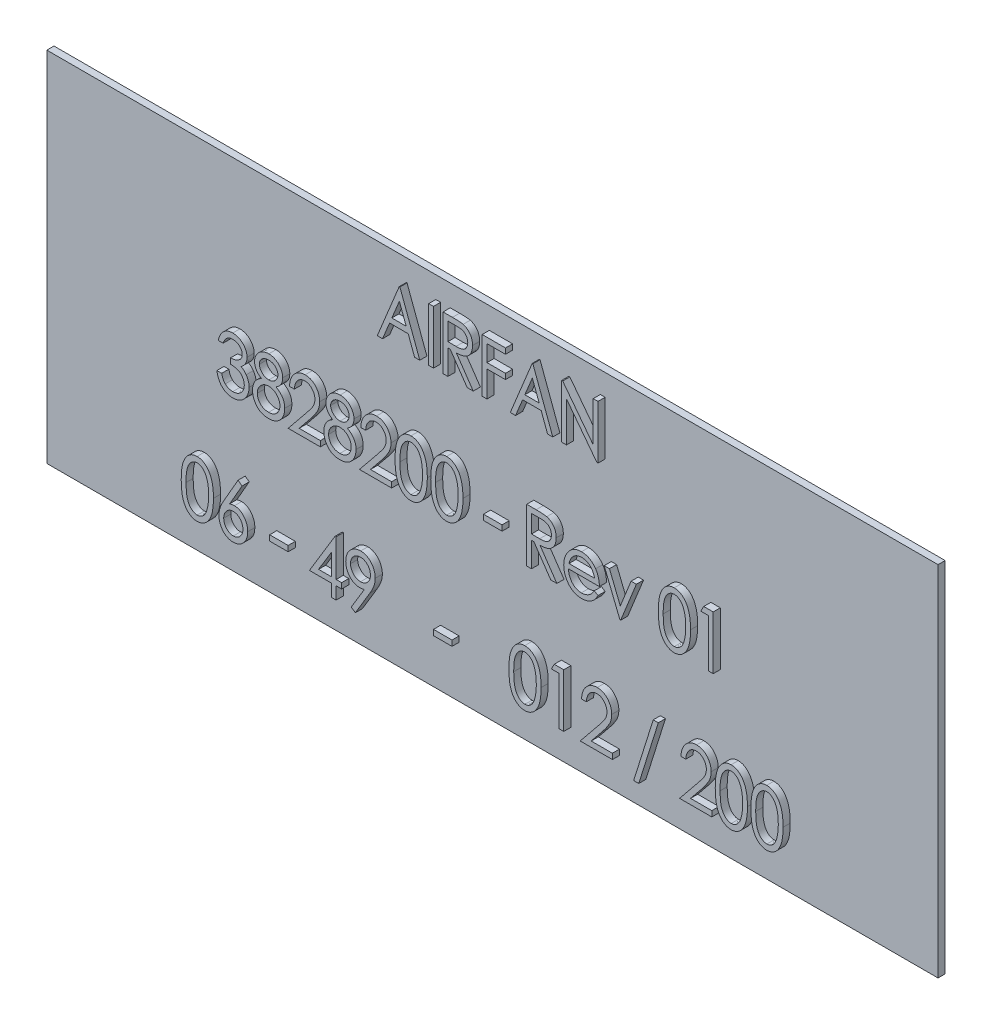
SolidWorks part; units mm, degrees
material "ABS"
ref_plane "Plan de face" through (0, 0, 0) normal (0, 0, 1) x (1, 0, 0)
ref_plane "Plan de dessus" through (0, 0, 0) normal (0, 1, 0) x (1, 0, 0)
ref_plane "Plan de droite" through (0, 0, 0) normal (1, 0, 0) x (0, 0, -1)
sketch "Esquisse1" plane through (0, 0, 0) normal (0, 0, 1) x (1, 0, 0)
  line L1 (-22.4844, -2.8351) -> (2.5156, -2.8351)
  line L2 (-22.4844, -2.8351) -> (-22.4844, -12.8776)
  line L3 (-22.4844, -12.8776) -> (2.5156, -12.8776)
  line L4 (2.5156, -2.8351) -> (2.5156, -12.8776)
  dimension "D1" = 10.0425
  dimension "D2" = 25
extrude "Extrusion1" add sketch "Esquisse1" along normal blind 0.2
sketch "Esquisse4" plane through (0, 0, 0.2) normal (0, 0, 1) x (1, 0, 0)
  text T0 "           AIRFAN\r\n  3828200 - Rev 01\r\n06 - 49   -   012 / 200" font "Century Gothic" height 1.5
extrude "Extrusion4" add sketch "Esquisse4" along normal blind 0.2
